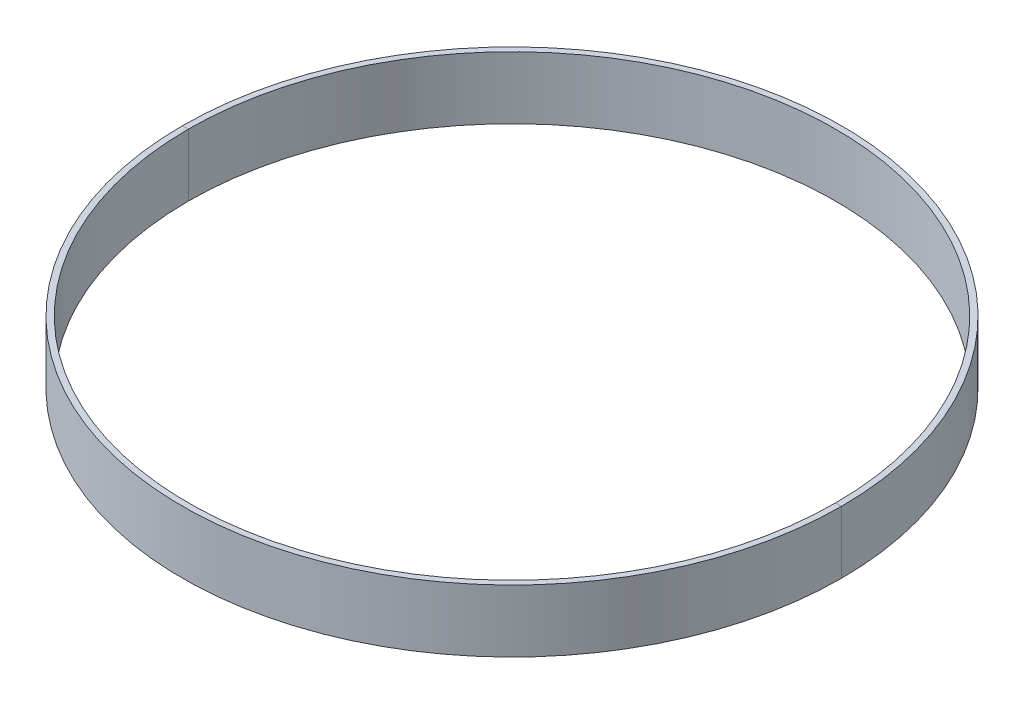
SolidWorks part; units mm, degrees
ref_plane "Front Plane" through (0, 0, 0) normal (0, 0, 1) x (1, 0, 0)
ref_plane "Top Plane" through (0, 0, 0) normal (0, 1, 0) x (1, 0, 0)
ref_plane "Right Plane" through (0, 0, 0) normal (1, 0, 0) x (0, 0, -1)
sketch "Sketch2" plane through (0, 0, 0) normal (0, 1, 0) x (1, 0, 0)
  line L0 (0, 0) -> (0, 184.9275) construction
  line L1 (-52.619, 127.0334) -> (-52.7956, 127.4598) construction
  line L2 (53.3608, 128.8244) -> (53.3991, 128.9168) construction
  line L3 (0, 0) -> (-52.619, 127.0334) construction
  line L4 (0, 0) -> (52.619, 127.0334) construction
  line L5 (-52.619, 127.0334) -> (-52.7956, 127.4598) construction
  line L6 (-53.0973, 128.1883) -> (-50.3257, 129.3363) construction
  line L7 (-53.3991, 128.9168) -> (-51.5513, 129.6821) construction
  line L8 (-51.2496, 128.9537) -> (-50.9478, 128.2252) construction
  line L9 (-50.9478, 128.2252) -> (-52.7956, 127.4598) construction
  line L10 (-52.8338, 127.5522) -> (-53.0973, 128.1883) construction
  line L11 (-53.3991, 128.9168) -> (-53.5757, 129.3431) construction
  line L12 (-52.8338, 127.5522) -> (-53.0973, 128.1883) construction
  line L13 (-53.3991, 128.9168) -> (-53.5757, 129.3431) construction
  line L14 (-53.0973, 128.1883) -> (-53.3608, 128.8244) construction
  line L15 (-53.0973, 128.1883) -> (-53.3608, 128.8244) construction
  line L22 (52.7956, 127.4598) -> (52.619, 127.0334) construction
  line L23 (53.5757, 129.3431) -> (53.3991, 128.9168) construction
  line L27 (53.3991, 128.9168) -> (53.3608, 128.8244) construction
  line L28 (52.8338, 127.5522) -> (52.7956, 127.4598) construction
  line L29 (-51.5513, 129.6821) -> (-51.2496, 128.9537) construction
  line L30 (-52.8338, 127.5522) -> (-53.0973, 128.1883) construction
  line L32 (53.3608, 128.8244) -> (52.8338, 127.5522) construction
  line L33 (128.8244, 53.3608) -> (127.5522, 52.8338) construction
  line L35 (127.5522, 52.8338) -> (127.4598, 52.7956) construction
  line L36 (127.4598, 52.7956) -> (127.0334, 52.619) construction
  line L37 (52.619, 127.0334) -> (52.7956, 127.4598) construction
  line L38 (53.3608, 128.8244) -> (53.3991, 128.9168) construction
  line L39 (53.3991, 128.9168) -> (53.5757, 129.3431) construction
  line L40 (129.3431, 53.5757) -> (128.9168, 53.3991) construction
  line L41 (128.9168, 53.3991) -> (128.8244, 53.3608) construction
  line L42 (128.8244, -53.3608) -> (127.5522, -52.8338) construction
  line L43 (127.5522, -52.8338) -> (127.4598, -52.7956) construction
  line L44 (127.4598, -52.7956) -> (127.0334, -52.619) construction
  line L45 (127.0334, 52.619) -> (127.4598, 52.7956) construction
  line L46 (128.8244, 53.3608) -> (128.9168, 53.3991) construction
  line L47 (128.9168, 53.3991) -> (129.3431, 53.5757) construction
  line L48 (129.3431, -53.5757) -> (128.9168, -53.3991) construction
  line L49 (128.9168, -53.3991) -> (128.8244, -53.3608) construction
  line L50 (53.3608, -128.8244) -> (52.8338, -127.5522) construction
  line L51 (52.8338, -127.5522) -> (52.7956, -127.4598) construction
  line L52 (52.7956, -127.4598) -> (52.619, -127.0334) construction
  line L53 (127.0334, -52.619) -> (127.4598, -52.7956) construction
  line L54 (128.8244, -53.3608) -> (128.9168, -53.3991) construction
  line L55 (128.9168, -53.3991) -> (129.3431, -53.5757) construction
  line L56 (53.5757, -129.3431) -> (53.3991, -128.9168) construction
  line L57 (53.3991, -128.9168) -> (53.3608, -128.8244) construction
  line L58 (-53.3608, -128.8244) -> (-52.8338, -127.5522) construction
  line L59 (-52.8338, -127.5522) -> (-52.7956, -127.4598) construction
  line L60 (-52.7956, -127.4598) -> (-52.619, -127.0334) construction
  line L61 (52.619, -127.0334) -> (52.7956, -127.4598) construction
  line L62 (53.3608, -128.8244) -> (53.3991, -128.9168) construction
  line L63 (53.3991, -128.9168) -> (53.5757, -129.3431) construction
  line L64 (-53.5757, -129.3431) -> (-53.3991, -128.9168) construction
  line L65 (-53.3991, -128.9168) -> (-53.3608, -128.8244) construction
  line L66 (-128.8244, -53.3608) -> (-127.5522, -52.8338) construction
  line L67 (-127.5522, -52.8338) -> (-127.4598, -52.7956) construction
  line L68 (-127.4598, -52.7956) -> (-127.0334, -52.619) construction
  line L69 (-52.619, -127.0334) -> (-52.7956, -127.4598) construction
  line L70 (-52.7956, -127.4598) -> (-52.8338, -127.5522) construction
  line L71 (-53.3991, -128.9168) -> (-53.5757, -129.3431) construction
  line L72 (-129.3431, -53.5757) -> (-128.9168, -53.3991) construction
  line L73 (-128.9168, -53.3991) -> (-128.8244, -53.3608) construction
  line L74 (-128.8244, 53.3608) -> (-127.5522, 52.8338) construction
  line L75 (-127.5522, 52.8338) -> (-127.5064, 52.8149) construction
  line L76 (-127.4598, 52.7956) -> (-127.0334, 52.619) construction
  line L77 (-127.0334, -52.619) -> (-127.4598, -52.7956) construction
  line L78 (-127.4598, -52.7956) -> (-127.5522, -52.8338) construction
  line L79 (-128.9168, -53.3991) -> (-129.3431, -53.5757) construction
  line L80 (-129.3431, 53.5757) -> (-128.9168, 53.3991) construction
  line L81 (-128.9168, 53.3991) -> (-128.8244, 53.3608) construction
  line L82 (-53.0973, 128.1883) -> (-52.8338, 127.5522) construction
  line L83 (-52.8338, 127.5522) -> (-52.7956, 127.4598) construction
  line L84 (-52.7956, 127.4598) -> (-52.619, 127.0334) construction
  line L85 (-127.0334, 52.619) -> (-127.4598, 52.7956) construction
  line L86 (-127.5064, 52.8149) -> (-127.5522, 52.8338) construction
  line L87 (-128.9168, 53.3991) -> (-129.3431, 53.5757) construction
  line L88 (-53.5757, 129.3431) -> (-53.3991, 128.9168) construction
  line L89 (-53.3991, 128.9168) -> (-53.3608, 128.8244) construction
  line L90 (-53.3608, 128.8244) -> (-53.3991, 128.9168) construction
  line L91 (-53.3608, 128.8244) -> (-53.3991, 128.9168) construction
  line L92 (-53.3608, 128.8244) -> (-53.3991, 128.9168) construction
  line L93 (-53.0973, 128.1883) -> (-53.3608, 128.8244) construction
  line L94 (-53.3608, 128.8244) -> (-53.0973, 128.1883) construction
  line L95 (-52.7956, 127.4598) -> (-52.8338, 127.5522) construction
  line L96 (-52.7956, 127.4598) -> (-52.8338, 127.5522) construction
  line L97 (-52.7956, 127.4598) -> (-52.8338, 127.5522) construction
  line L98 (52.619, 127.0334) -> (52.7956, 127.4598) construction
  line L99 (52.7956, 127.4598) -> (52.8338, 127.5522) construction
  line L100 (52.7956, 127.4598) -> (52.8338, 127.5522) construction
  line L101 (52.8338, 127.5522) -> (53.3608, 128.8244) construction
  line L102 (52.8338, 127.5522) -> (53.3608, 128.8244) construction
  line L103 (53.3991, 128.9168) -> (53.5757, 129.3431) construction
  line L104 (127.4598, 52.7956) -> (127.5522, 52.8338) construction
  line L105 (127.5522, 52.8338) -> (128.8244, 53.3608) construction
  line L106 (127.4598, -52.7956) -> (127.5522, -52.8338) construction
  line L107 (127.5522, -52.8338) -> (128.8244, -53.3608) construction
  line L108 (52.7956, -127.4598) -> (52.8338, -127.5522) construction
  line L109 (52.8338, -127.5522) -> (53.3608, -128.8244) construction
  line L110 (-53.3608, -128.8244) -> (-53.3991, -128.9168) construction
  line L111 (-52.8338, -127.5522) -> (-53.3608, -128.8244) construction
  line L112 (-128.8244, -53.3608) -> (-128.9168, -53.3991) construction
  line L113 (-127.5522, -52.8338) -> (-128.8244, -53.3608) construction
  line L114 (-127.5522, 52.8338) -> (-128.8244, 53.3608) construction
  line L115 (-128.8244, 53.3608) -> (-128.9168, 53.3991) construction
  line L116 (-127.4598, 52.7956) -> (-127.5064, 52.8149) construction
  arc A0 (53.5757, 129.3431) -> (-53.5757, 129.3431) centre (0, 0) ccw
  arc A1 (52.619, 127.0334) -> (-52.619, 127.0334) centre (0, 0) ccw
  arc A2 (-52.619, 127.0334) -> (52.619, 127.0334) centre (0, 0) ccw construction
  arc A3 (-53.5757, 129.3431) -> (53.5757, 129.3431) centre (0, 0) ccw construction
  arc A4 (127.0334, 52.619) -> (52.619, 127.0334) centre (0, 0) ccw
  arc A5 (129.3431, 53.5757) -> (53.5757, 129.3431) centre (0, 0) ccw
  arc A6 (127.0334, -52.619) -> (127.0334, 52.619) centre (0, 0) ccw
  arc A7 (129.3431, -53.5757) -> (129.3431, 53.5757) centre (0, 0) ccw
  arc A8 (52.619, -127.0334) -> (127.0334, -52.619) centre (0, 0) ccw
  arc A9 (53.5757, -129.3431) -> (129.3431, -53.5757) centre (0, 0) ccw
  arc A10 (-52.619, -127.0334) -> (52.619, -127.0334) centre (0, 0) ccw
  arc A11 (-53.5757, -129.3431) -> (53.5757, -129.3431) centre (0, 0) ccw
  arc A12 (-127.0334, -52.619) -> (-52.619, -127.0334) centre (0, 0) ccw
  arc A13 (-129.3431, -53.5757) -> (-53.5757, -129.3431) centre (0, 0) ccw
  arc A14 (-127.0334, 52.619) -> (-127.0334, -52.619) centre (0, 0) ccw
  arc A15 (-129.3431, 53.5757) -> (-129.3431, -53.5757) centre (0, 0) ccw
  arc A16 (-52.619, 127.0334) -> (-127.0334, 52.619) centre (0, 0) ccw
  arc A17 (-53.5757, 129.3431) -> (-129.3431, 53.5757) centre (0, 0) ccw
  point P18 (52.7956, 127.4598)
  point P19 (53.3991, 128.9168)
  point P93 (0, 0)
  dimension "D1" = 280
  dimension "D2" = 275
  dimension "D3" = 8
  dimension "D4" = 3
  dimension "D5" = 1.577
  dimension "D6" = 2
  dimension "D7" = 1.25
extrude "Boss-Extrude1" add sketch "Sketch2" along normal mid plane 26.5
split "Split1" trim tools "Front Plane" bodies to split 101 resulting bodies 103 104
